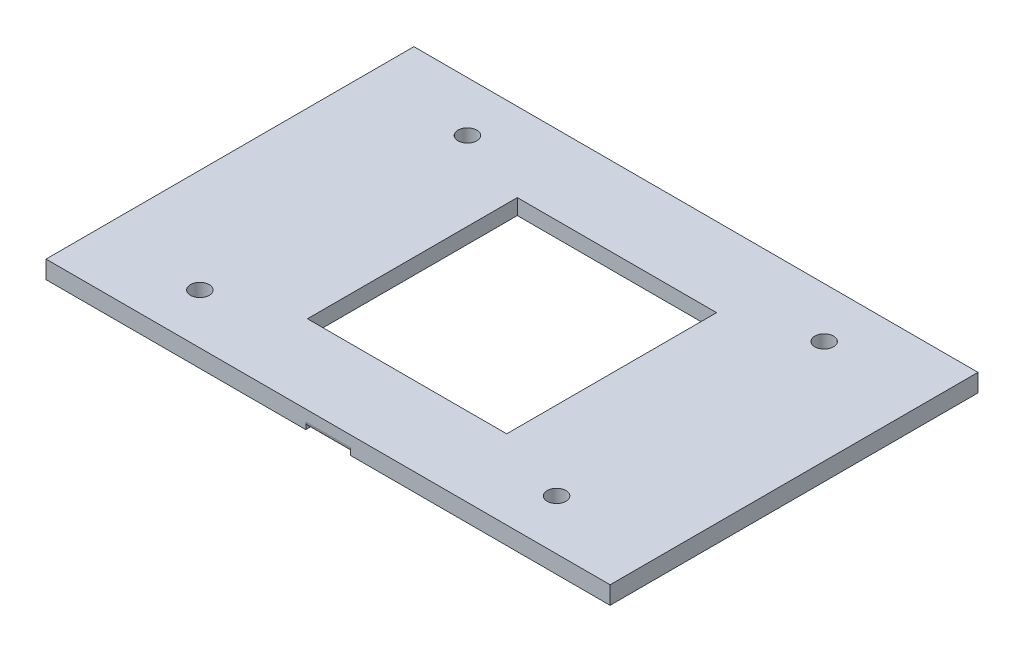
SolidWorks part; units mm, degrees
ref_plane "Спереди" through (0, 0, 0) normal (0, 0, 1) x (1, 0, 0)
ref_plane "Сверху" through (0, 0, 0) normal (0, 1, 0) x (1, 0, 0)
ref_plane "Справа" through (0, 0, 0) normal (1, 0, 0) x (0, 0, -1)
ref_plane "Плоскость4" through (0, 60.646, 0) normal (0, -1, 0) x (-1, 0, 0)
sketch "Эскиз1" plane through (0, 60.646, 0) normal (0, -1, 0) x (-1, 0, 0)
  line L0 (-128.059, -48.2731) -> (-128.059, -130.7731)
  line L1 (-128.059, -130.7731) -> (-1.559, -130.7731)
  line L2 (-1.559, -130.7731) -> (-1.559, -48.2731)
  line L3 (-1.559, -48.2731) -> (-128.059, -48.2731)
  line L4 (-87.1513, -65.9891) -> (-87.1513, -113.0572)
  line L5 (-87.1513, -113.0572) -> (-42.4667, -113.0572)
  line L6 (-42.4667, -113.0572) -> (-42.4667, -65.9891)
  line L7 (-42.4667, -65.9891) -> (-87.1513, -65.9891)
  circle A0 centre (-24.809, -59.5231) radius 2.1
  circle A1 centre (-104.809, -59.5231) radius 2.1
  circle A2 centre (-24.809, -119.5231) radius 2.1
  circle A3 centre (-104.809, -119.5231) radius 2.1
  point P18 (0, 0)
  point P29 (0, 0)
  point P30 (0, 0)
  point P31 (-87.1513, -65.9891)
  point P33 (0, 0)
  point P34 (-42.4667, -113.0572)
extrude "Бобышка-Вытянуть1" add sketch "Эскиз1" along normal blind 4
ref_plane "Плоскость5" through (0, 56.646, 0) normal (0, -1, 0) x (-1, 0, 0)
sketch "Эскиз3" plane through (0, 56.646, 0) normal (0, -1, 0) x (-1, 0, 0)
  line L1 (-32.809, -57.5231) -> (-32.809, -84.5231)
  line L6 (-59.809, -57.5231) -> (-59.809, -48.2731)
  line L7 (-1.559, -48.2731) -> (-128.059, -48.2731) construction
  line L9 (-69.809, -57.5231) -> (-69.809, -48.2731)
  line L10 (-69.809, -48.2731) -> (-59.809, -48.2731)
  line L11 (-69.809, -121.5231) -> (-69.809, -130.7731)
  line L12 (-128.059, -130.7731) -> (-1.559, -130.7731) construction
  line L13 (-69.809, -130.7731) -> (-59.809, -130.7731)
  line L14 (-59.809, -130.7731) -> (-59.809, -121.5231)
  line L15 (-96.809, -121.5231) -> (-96.809, -94.5231)
  line L16 (-96.809, -84.5231) -> (-116.809, -84.5231)
  line L17 (-116.809, -84.5231) -> (-116.809, -94.5231)
  line L18 (-116.809, -94.5231) -> (-96.809, -94.5231)
  line L19 (-32.809, -94.5231) -> (-32.809, -121.5231)
  line L20 (-32.809, -94.5231) -> (-12.809, -94.5231)
  line L21 (-12.809, -94.5231) -> (-12.809, -84.5231)
  line L22 (-12.809, -84.5231) -> (-32.809, -84.5231)
  line L23 (-32.809, -121.5231) -> (-59.809, -121.5231)
  line L24 (-59.809, -130.7731) -> (-69.809, -130.7731)
  line L25 (-69.809, -121.5231) -> (-96.809, -121.5231)
  line L26 (-96.809, -84.5231) -> (-96.809, -57.5231)
  line L27 (-96.809, -57.5231) -> (-69.809, -57.5231)
  line L28 (-59.809, -57.5231) -> (-32.809, -57.5231)
extrude "Вырез-Вытянуть1" cut sketch "Эскиз3" against normal blind 0.5 contours L28 L6 L10 L9 L27 L26 L16 L17 L18 L15 L25 L11 L13 L14 L23 L19 L20 L21 L22 L1
fillet "Скругление1" radius 1 2 edges at (64.809, 57.146, 48.2731) (64.809, 57.146, 130.7731)
